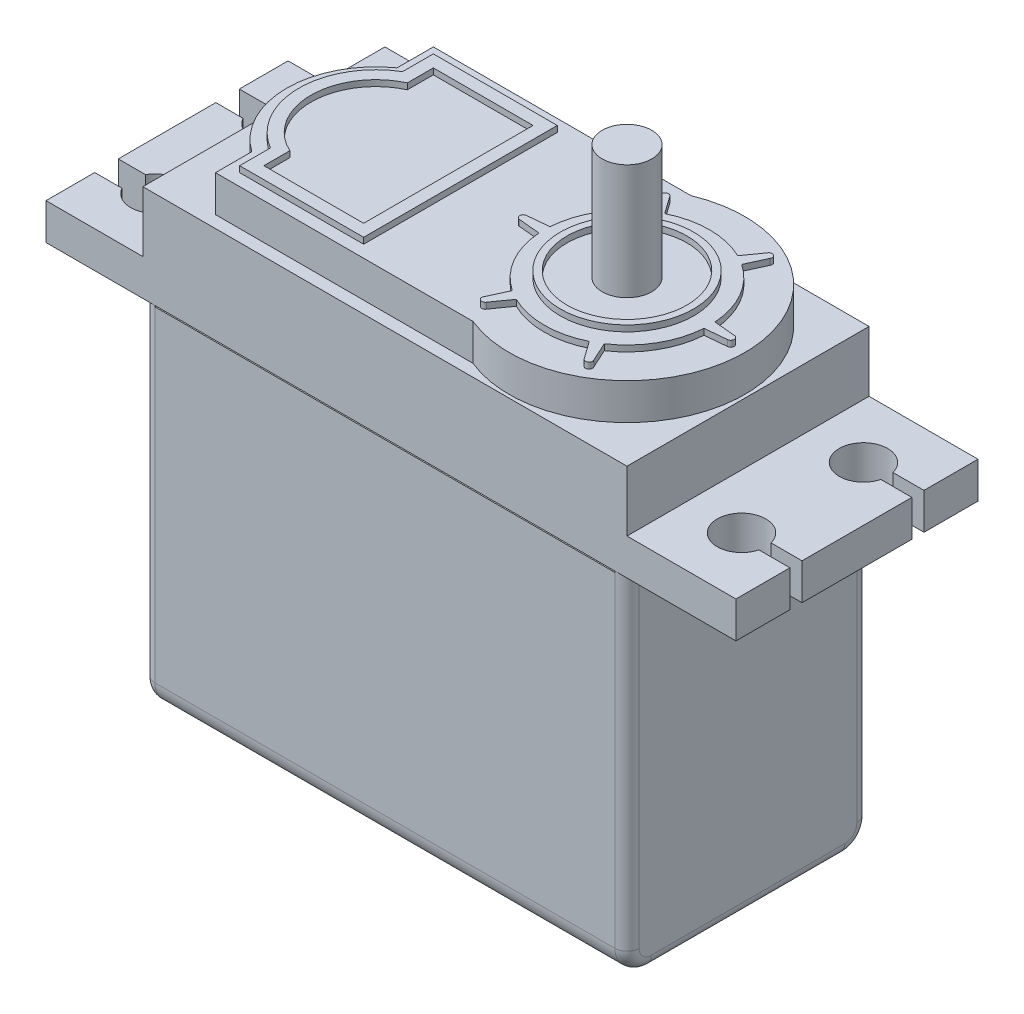
SolidWorks part; units mm, degrees
ref_plane "Front Plane" through (0, 0, 0) normal (0, 0, 1) x (1, 0, 0)
ref_plane "Top Plane" through (0, 0, 0) normal (0, 1, 0) x (1, 0, 0)
ref_plane "Right Plane" through (0, 0, 0) normal (1, 0, 0) x (0, 0, -1)
sketch "Sketch1" plane through (0, 0, 0) normal (0, 1, 0) x (1, 0, 0)
  line L0 (-25.7246, 0) -> (31.2754, 0)
  line L1 (22.2754, -20) -> (22.2754, 0)
  line L2 (-17.7246, -20) -> (-17.7246, 0)
  line L3 (-25.7246, -20) -> (31.2754, -20)
  line L4 (31.2754, 0) -> (31.2754, -20)
  line L7 (-25.7246, -20) -> (-25.7246, 0)
  dimension "D1" = 57
  dimension "D2" = 9
  dimension "D3" = 8
  dimension "D4" = 40
  dimension "D5" = 20
ref_plane "Plane1" through (0, 10, 0) normal (0, 1, 0) x (1, 0, 0)
sketch "Sketch2" plane through (0, 10, 0) normal (0, 1, 0) x (1, 0, 0)
  line L0 (31.2754, 0) -> (31.2754, -20) construction
  line L1 (22.2754, -20) -> (22.2754, 0) construction
  line L2 (-25.7246, -20) -> (31.2754, -20) construction
  line L3 (-25.7246, -20) -> (-25.7246, 0) construction
  line L4 (-17.7246, -20) -> (-17.7246, 0) construction
  line L5 (-25.7246, 0) -> (31.2754, 0) construction
  line L6 (31.2754, 0) -> (31.2754, -20)
  line L7 (22.2754, -20) -> (22.2754, 0)
  line L8 (-25.7246, -20) -> (31.2754, -20)
  line L9 (-25.7246, -20) -> (-25.7246, 0)
  line L10 (-17.7246, -20) -> (-17.7246, 0)
  line L11 (-25.7246, 0) -> (31.2754, 0)
extrude "Boss-Extrude2" add sketch "Sketch1" along normal blind 3 contours L3 L4 L0 L7
sketch "Sketch3" plane through (0, 0, 0) normal (0, -1, 0) x (1, 0, 0)
  line L0 (22.2754, 20) -> (22.2754, 0) construction
  line L1 (-17.7246, 20) -> (-17.7246, 0) construction
  line L2 (22.2754, 20) -> (22.2754, 0)
  line L3 (-17.7246, 20) -> (-17.7246, 0)
  line L4 (-17.7246, 20) -> (22.2754, 20)
  line L5 (-17.7246, 0) -> (22.2754, 0)
extrude "Boss-Extrude3" add sketch "Sketch3" along normal blind 27
sketch "Sketch4" plane through (0, 3, 0) normal (0, 1, 0) x (1, 0, 0)
  line L0 (22.2754, -20) -> (22.2754, 0) construction
  line L1 (-17.7246, -20) -> (-17.7246, 0) construction
  line L2 (22.2754, -20) -> (22.2754, 0)
  line L3 (-17.7246, -20) -> (-17.7246, 0)
  line L4 (-17.7246, -20) -> (22.2754, -20)
  line L5 (-17.7246, 0) -> (22.2754, 0)
extrude "Boss-Extrude4" add sketch "Sketch4" along normal blind 5
sketch "Sketch7" plane through (0, 8, 0) normal (0, 1, 0) x (1, 0, 0)
  line L0 (22.2754, -10) -> (12.2754, -10) construction
  line L1 (22.2754, -20) -> (22.2754, 0) construction
  line L5 (8.5553, -1) -> (-12.7246, -1)
  line L6 (8.5553, -19) -> (-12.7246, -19)
  line L7 (-12.7246, -10) -> (-15.7246, -10) construction
  line L8 (-12.7246, -19) -> (-12.7246, -16)
  line L9 (-12.7246, -1) -> (-12.7246, -4)
  circle A0 centre (12.2754, -10) radius 2.0498
  arc A1 (-12.7246, -16) -> (-12.7246, -4) centre (-8.4811, -10) cw
  arc A2 (8.5553, -19) -> (8.5553, -1) centre (12.2754, -10) ccw
  dimension "D1" = 10
  dimension "D4" = 3
  dimension "D5" = 3
  dimension "D6" = 3
extrude "Boss-Extrude5" add sketch "Sketch7" along normal blind 3
sketch "Sketch8" plane through (0, -27, 0) normal (0, -1, 0) x (1, 0, 0)
  line L4 (22.2754, 20) -> (-17.7246, 20)
  line L5 (-17.7246, 20) -> (-17.7246, 0)
  line L6 (-17.7246, 0) -> (22.2754, 0)
  line L7 (22.2754, 0) -> (22.2754, 20)
  line L8 (22.2754, 20) -> (-17.7246, 20)
  line L9 (-17.7246, 20) -> (-17.7246, 0)
  line L10 (-17.7246, 0) -> (22.2754, 0)
  line L11 (22.2754, 0) -> (22.2754, 20)
  dimension "D1" = 0
extrude "Boss-Extrude6" add sketch "Sketch8" along normal blind 2
fillet "Fillet1" radius 2 2 edges at (2.2754, -29, 20) (2.2754, -29, 0)
fillet "Fillet3" radius 1 10 edges at (22.2754, -13.5, 0) (22.2754, -28.4142, 0.5858) (22.2754, -13.5, 20) (22.2754, -28.4142, 19.4142) (-17.7246, -13.5, 20) (-17.7246, -28.4142, 19.4142) (-17.7246, -13.5, 0) (-17.7246, -28.4142, 0.5858) (22.2754, -29, 10) (-17.7246, -29, 10)
sketch "Sketch9" plane through (0, 3, 0) normal (0, 1, 0) x (1, 0, 0)
  line L0 (-17.7246, -10) -> (-21.7246, -10) construction
  line L1 (-17.7246, 0) -> (-17.7246, -20) construction
  line L2 (-21.7246, -10) -> (-21.7246, -15) construction
  line L3 (-21.7246, -10) -> (-21.7246, -5) construction
  line L4 (-23.7246, -15) -> (-25.7246, -15) construction
  line L5 (-25.7246, -20) -> (-25.7246, 0) construction
  line L6 (-23.7246, -5) -> (-25.7246, -5) construction
  line L7 (-25.7246, -15.9745) -> (-25.7246, -14.0291)
  line L8 (-23.4711, -4.0255) -> (-25.7246, -4.0255)
  line L9 (-23.4711, -15.9745) -> (-25.7246, -15.9745)
  line L10 (-23.4732, -14.0291) -> (-25.7246, -14.0291)
  line L11 (-23.4732, -5.9709) -> (-25.7246, -5.9709)
  line L12 (-25.7246, -4.0255) -> (-25.7246, -5.9709)
  arc A0 (-23.4711, -15.9745) -> (-23.4732, -14.0291) centre (-21.7246, -15) ccw
  arc A2 (-23.4711, -4.0255) -> (-23.4732, -5.9709) centre (-21.7246, -5) cw
  dimension "D4" = 4
  dimension "D1" = 4
  dimension "D2" = 5
extrude "Cut-Extrude1" cut sketch "Sketch9" against normal blind 12
sketch "Sketch11" plane through (0, 3, 0) normal (0, 1, 0) x (1, 0, 0)
  line L0 (31.2754, -10) -> (26.7754, -10) construction
  line L1 (31.2754, 0) -> (31.2754, -20) construction
  line L2 (26.7754, -10) -> (26.7754, -14.998) construction
  line L3 (26.7754, -10) -> (26.7754, -4.9623) construction
  line L4 (31.2754, -5.4623) -> (31.2754, -4.4623)
  line L5 (28.7119, -14.5377) -> (31.2754, -14.5377)
  line L6 (28.7119, -15.5377) -> (31.2754, -15.5377)
  line L7 (28.7119, -5.4623) -> (31.2754, -5.4623)
  line L8 (28.7119, -4.4623) -> (31.2754, -4.4623)
  line L9 (31.2754, -14.5377) -> (31.2754, -15.5377)
  arc A0 (28.7119, -4.4623) -> (28.7119, -5.4623) centre (26.7754, -4.9623) ccw
  arc A1 (28.7119, -15.5377) -> (28.7119, -14.5377) centre (26.7754, -15.0377) cw
  dimension "D2" = 4
  dimension "D1" = 4.5
extrude "Cut-Extrude2" cut sketch "Sketch11" against normal blind 12
sketch "Sketch12" plane through (0, 11, 0) normal (0, 1, 0) x (1, 0, 0)
  circle A0 centre (12.2754, -10) radius 2.0498 construction
  circle A1 centre (12.2754, -10) radius 2.0498
extrude "Boss-Extrude7" add sketch "Sketch12" along normal blind 10 separate body
sketch "Sketch13" plane through (0, 0, 20) normal (0, 0, 1) x (1, 0, 0)
  line L0 (-16.7246, 0) -> (21.2754, 0) construction
  line L1 (21.2754, -27) -> (21.2754, 0) construction
  line L2 (-16.7246, 0) -> (21.2754, 0)
  line L3 (-16.7246, 0) -> (-16.7246, -0.1)
  line L4 (-16.7246, -0.1) -> (21.2754, -0.1)
  line L5 (21.2754, 0) -> (21.2754, -0.1)
  dimension "D1" = 0.1
extrude "Cut-Extrude3" cut sketch "Sketch13" against normal blind 0.1
sketch "Sketch14" plane through (22.2754, 0, 0) normal (1, 0, 0) x (0, 0, -1)
  line L0 (-1, -27) -> (-1, 0) construction
  line L1 (-19, 0) -> (-1, 0)
  line L2 (-19, 0) -> (-19, -0.1)
  line L3 (-19, -0.1) -> (-1, -0.1)
  line L4 (-1, 0) -> (-1, -0.1)
  dimension "D1" = 0.1
extrude "Cut-Extrude4" cut sketch "Sketch14" against normal blind 0.1
sketch "Sketch15" plane through (0, 0, 0) normal (0, 0, -1) x (-1, 0, 0)
  line L0 (16.7246, -27) -> (16.7246, 0) construction
  line L1 (-21.2754, 0) -> (16.7246, 0)
  line L2 (-21.2754, 0) -> (-21.2754, -0.1)
  line L3 (-21.2754, -0.1) -> (16.7246, -0.1)
  line L4 (16.7246, 0) -> (16.7246, -0.1)
  dimension "D1" = 0.1
sketch "Sketch16" plane through (-17.7246, 0, 0) normal (-1, 0, 0) x (0, 0, 1)
  line L0 (19, -27) -> (19, 0) construction
  line L1 (1, 0) -> (19, 0)
  line L2 (1, 0) -> (1, -0.1)
  line L3 (1, -0.1) -> (19, -0.1)
  line L4 (19, 0) -> (19, -0.1)
  dimension "D1" = 0.1
extrude "Boss-Extrude10" add sketch "Sketch16" along normal blind 0.1
sketch "Sketch17" plane through (0, 11, 0) normal (0, 1, 0) x (1, 0, 0)
  line L0 (19.1051, -10) -> (20.8501, -10) construction
  line L1 (20.8501, -10) -> (19.1051, -10) construction
  line L6 (20.8501, -10.2889) -> (19.0899, -10.4542)
  line L7 (20.8501, -9.7111) -> (19.0899, -9.5458)
  line L8 (16.3126, -17.5704) -> (15.2893, -16.1287)
  line L9 (16.8129, -17.2815) -> (16.076, -15.6745)
  line L10 (7.7378, -17.2815) -> (8.4747, -15.6745)
  line L11 (8.2381, -17.5704) -> (9.2615, -16.1287)
  line L12 (3.7006, -9.7111) -> (5.4608, -9.5458)
  line L13 (3.7006, -10.2889) -> (5.4608, -10.4542)
  line L14 (8.2381, -2.4296) -> (9.2615, -3.8713)
  line L15 (7.7378, -2.7185) -> (8.4747, -4.3255)
  line L16 (16.8129, -2.7185) -> (16.076, -4.3255)
  line L17 (16.3126, -2.4296) -> (15.2893, -3.8713)
  arc A0 (19.0899, -9.5458) -> (16.076, -4.3255) centre (12.2754, -10) ccw
  arc A3 (20.8501, -10.2889) -> (20.8501, -9.7111) centre (20.8501, -10) ccw
  arc A5 (16.3126, -17.5704) -> (16.8129, -17.2815) centre (16.5627, -17.426) ccw
  arc A6 (7.7378, -17.2815) -> (8.2381, -17.5704) centre (7.988, -17.426) ccw
  arc A7 (3.7006, -9.7111) -> (3.7006, -10.2889) centre (3.7006, -10) ccw
  arc A8 (8.2381, -2.4296) -> (7.7378, -2.7185) centre (7.988, -2.574) ccw
  arc A9 (16.8129, -2.7185) -> (16.3126, -2.4296) centre (16.5627, -2.574) ccw
  arc A10 (16.076, -15.6745) -> (19.0899, -10.4542) centre (12.2754, -10) ccw
  arc A11 (9.2615, -16.1287) -> (15.2893, -16.1287) centre (12.2754, -10) ccw
  arc A12 (5.4608, -10.4542) -> (8.4747, -15.6745) centre (12.2754, -10) ccw
  arc A13 (8.4747, -4.3255) -> (5.4608, -9.5458) centre (12.2754, -10) ccw
  arc A14 (15.2893, -3.8713) -> (9.2615, -3.8713) centre (12.2754, -10) ccw
  point P5 (19.9776, -10)
  point P37 (12.2754, -10)
  dimension "D1" = 6
extrude "Boss-Extrude13" add sketch "Sketch17" along normal blind 0.5
sketch "Sketch18" plane through (0, 11.5, 0) normal (0, 1, 0) x (1, 0, 0)
  circle A0 centre (12.2754, -10) radius 5.5057
  circle A1 centre (12.2754, -10) radius 4.954
extrude "Boss-Extrude14" add sketch "Sketch18" along normal blind 0.5
sketch "Sketch20" plane through (0, 11, 0) normal (0, 1, 0) x (1, 0, 0)
  line L16 (-1.4826, -18) -> (-1.4826, -2)
  line L17 (-2.4826, -3) -> (-10.7246, -3)
  line L18 (-10.7246, -3) -> (-10.7246, -5.1443)
  line L19 (-10.7246, -14.8557) -> (-10.7246, -17)
  line L20 (8.7595, -2) -> (-11.7246, -2)
  line L21 (-11.7246, -2) -> (-11.7246, -4.5421)
  line L22 (-11.7246, -15.4579) -> (-11.7246, -18)
  line L23 (-11.7246, -18) -> (8.7595, -18)
  line L24 (-1.4826, -2) -> (-11.7246, -2)
  line L25 (-11.7246, -2) -> (-11.7246, -4.5421)
  line L26 (-11.7246, -15.4579) -> (-11.7246, -18)
  line L27 (-11.7246, -18) -> (-1.4826, -18)
  line L28 (-10.7246, -17) -> (-2.4826, -17)
  line L29 (-2.4826, -17) -> (-2.4826, -3)
  arc A8 (-10.7246, -5.1443) -> (-10.7246, -14.8557) centre (-8.4811, -10) ccw
  arc A10 (8.7595, -18) -> (8.7595, -2) centre (12.2754, -10) ccw
  arc A11 (-11.7246, -4.5421) -> (-11.7246, -15.4579) centre (-8.4811, -10) ccw
  arc A13 (-11.7246, -4.5421) -> (-11.7246, -15.4579) centre (-8.4811, -10) ccw
  dimension "D1" = 1
  dimension "D2" = 1
extrude "Boss-Extrude15" add sketch "Sketch20" along normal blind 0.5
sketch "Sketch22" plane through (0, 21, 0) normal (0, 1, 0) x (1, 0, 0)
  circle A0 centre (12.2754, -10) radius 2.0498
extrude "Boss-Extrude17" add sketch "Sketch22" along normal blind 0.01
